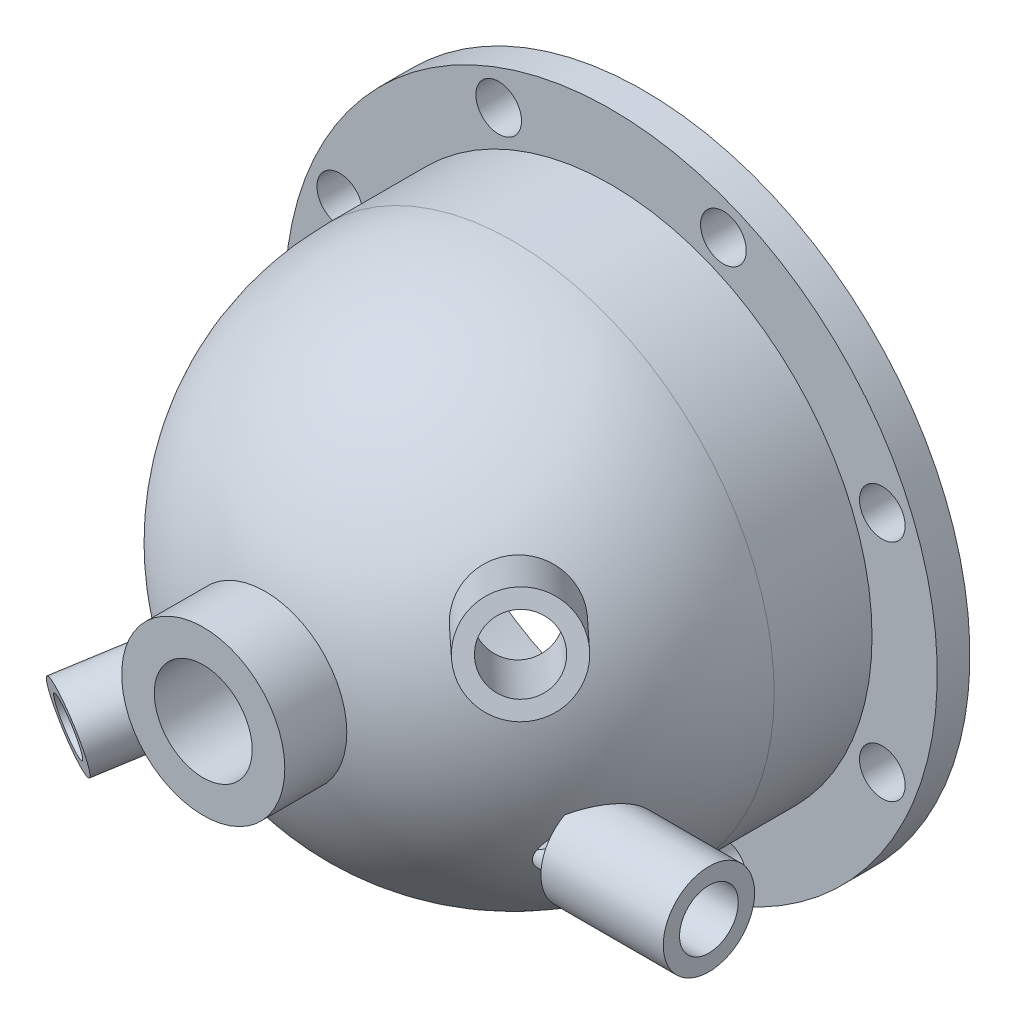
SolidWorks part; units mm, degrees
ref_plane "前视基准面" through (0, 0, 0) normal (0, 0, 1) x (1, 0, 0)
ref_plane "上视基准面" through (0, 0, 0) normal (0, 1, 0) x (1, 0, 0)
ref_plane "右视基准面" through (0, 0, 0) normal (1, 0, 0) x (0, 0, -1)
sketch "草图1" plane through (0, 0, 0) normal (0, 1, 0) x (1, 0, 0)
  line L0 (0, 40) -> (0, -95) construction
  line L1 (72, 40) -> (100, 40)
  line L2 (100, 40) -> (100, 30)
  line L3 (100, 30) -> (80, 30)
  line L4 (80, 30) -> (80, 0)
  line L5 (0, -80) -> (0, -72)
  line L6 (72, 0) -> (72, 30)
  line L7 (72, 30) -> (72, 40)
  arc A0 (80, 0) -> (0, -80) centre (-0.0001, 0.0001) cw
  arc A1 (0, -72) -> (72, 0) centre (0, 0) ccw
revolve "旋转1" add sketch "草图1" angle 360 about L0
sketch3d "3D草图1"
  line L0 (49.0926, 28.3436, 47.5663) -> (72.9755, 42.1324, 70.7066)
sweep "扫描2" add path "3D草图1" circular profile diameter 30 parameters "D3"=30
sketch3d "3D草图2"
  line L0 (-32.0429, -18.5, 64.0859) -> (-45.4663, -26.25, 90.9327)
sweep "扫描4" add path "3D草图2" circular profile diameter 24 parameters "D3"=24
sketch3d "3D草图3"
  line L0 (62.5, -30, 40) -> (100, -30, 40)
sweep "扫描6" add path "3D草图3" circular profile diameter 28 parameters "D3"=28
sketch3d "3D草图4"
  line L0 (0, 0, 74) -> (0, 0, 95)
sweep "扫描8" add path "3D草图4" circular profile diameter 50 parameters "D3"=50
sketch3d "3D草图5"
  line L0 (-3.3171, -1.9151, -3.2139) -> (72.9755, 42.1324, 70.7066)
sweep "切除-扫描2" cut path "3D草图5" circular profile diameter 20 parameters "D3"=20
sketch3d "3D草图6"
  line L0 (2.1651, 1.25, -4.3301) -> (-45.4663, -26.25, 90.9327)
sweep "切除-扫描4" cut path "3D草图6" circular profile diameter 16 parameters "D3"=16
sketch3d "3D草图7"
  line L0 (-20, -30, 40) -> (100, -30, 40)
sweep "切除-扫描6" cut path "3D草图7" circular profile diameter 18 parameters "D3"=18
sketch3d "3D草图8"
  line L0 (0, 0, -10) -> (0, 0, 95)
sweep "切除-扫描8" cut path "3D草图8" circular profile diameter 30 parameters "D3"=30
ref_plane "基准面1" through (0, 0, -40) normal (0, 0, 1) x (1, 0, 0)
sketch "草图20" plane through (0, 0, -40) normal (0, 0, 1) x (1, 0, 0)
  circle A0 centre (83.1492, 34.4415) radius 7
  circle A1 centre (34.4415, 83.1492) radius 7
  circle A2 centre (-34.4415, 83.1492) radius 7
  circle A3 centre (-83.1492, 34.4415) radius 7
  circle A4 centre (-83.1492, -34.4415) radius 7
  circle A5 centre (-34.4415, -83.1492) radius 7
  circle A6 centre (34.4415, -83.1492) radius 7
  circle A7 centre (83.1492, -34.4415) radius 7
extrude "切除-拉伸2" cut sketch "草图20" along normal blind 11
